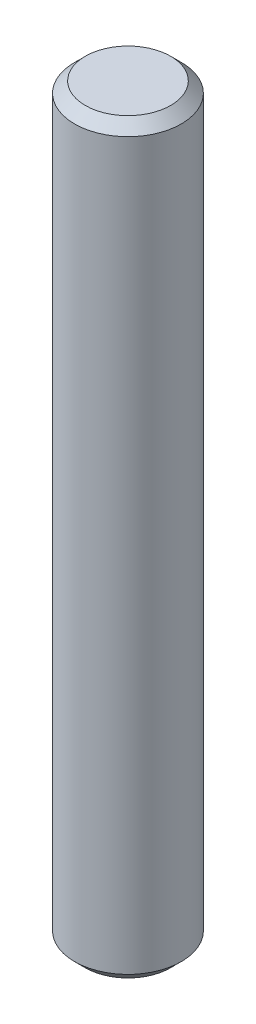
SolidWorks part; units mm, degrees
material "AISI 316 Annealed Stainless Steel Bar (SS)"
ref_plane "Front Plane" through (0, 0, 0) normal (0, 0, 1) x (1, 0, 0)
ref_plane "Top Plane" through (0, 0, 0) normal (0, 1, 0) x (1, 0, 0)
ref_plane "Right Plane" through (0, 0, 0) normal (1, 0, 0) x (0, 0, -1)
sketch "Sketch1" plane through (0, 0, 0) normal (0, 1, 0) x (1, 0, 0)
  circle A0 centre (0, 0) radius 3.175
  dimension "D1" = 6.35
extrude "Boss-Extrude1" add sketch "Sketch1" along normal blind 44.45
chamfer "Chamfer1" distance 0.635 angle 45 2 edges at (0, 0, 3.175) (0, 44.45, 3.175)
